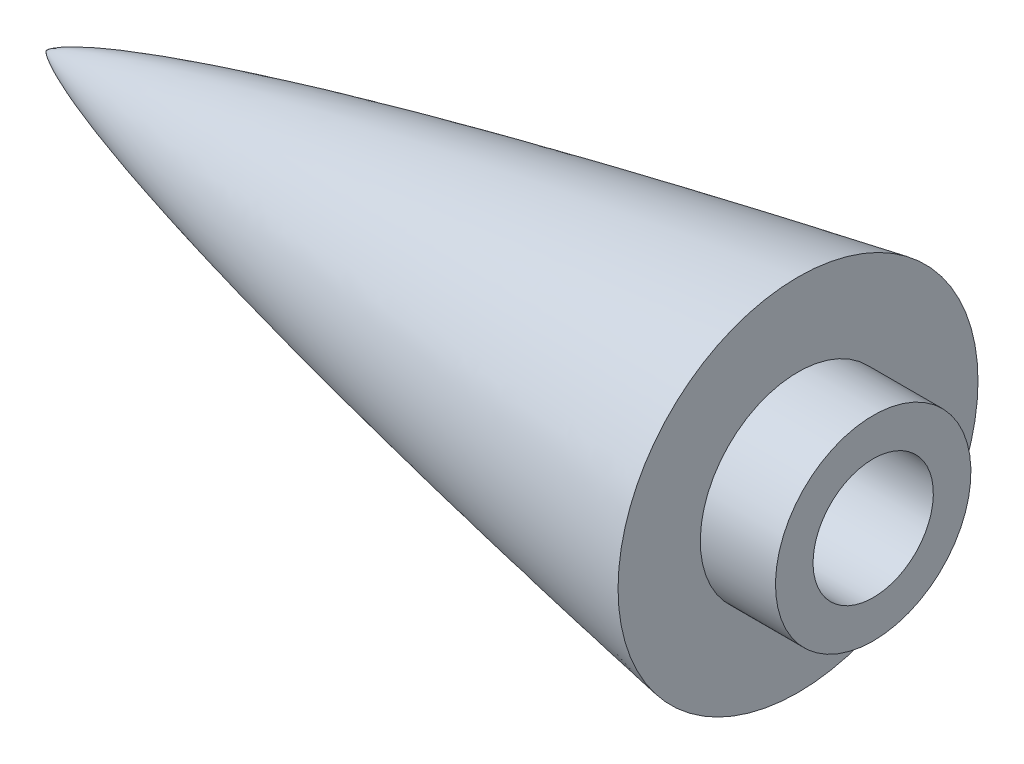
SolidWorks part; units mm, degrees
ref_plane "Front Plane" through (0, 0, 0) normal (0, 0, 1) x (1, 0, 0)
ref_plane "Top Plane" through (0, 0, 0) normal (0, 1, 0) x (1, 0, 0)
ref_plane "Right Plane" through (0, 0, 0) normal (1, 0, 0) x (0, 0, -1)
sketch "Sketch1" plane through (0, 0, 0) normal (0, 0, 1) x (1, 0, 0)
  line L0 (0.0769, 0) -> (19.7291, 0)
  line L1 (63.5769, 15.2023) -> (63.5769, 10.737)
  line L2 (63.5769, 10.737) -> (63.5769, 8.255)
  line L3 (63.5769, 8.255) -> (69.9269, 8.255)
  line L7 (19.7291, 0) -> (69.9269, 0)
  line L9 (69.9269, 8.255) -> (69.9269, 0)
  spline S0 degree 4 poles (0.0769, 0) (0.079, 0.0067) (0.0845, 0.0193) (0.099, 0.0402) (0.1222, 0.0682) (0.154, 0.101) (0.2002, 0.1434) (0.2682, 0.1995) (0.378, 0.2804) (0.559, 0.3995) (0.8654, 0.5781) (1.3931, 0.8496) (2.3104, 1.2634) (3.7858, 1.8459) (6.2747, 2.712) (9.6862, 3.7551) (13.8397, 4.9) (18.5275, 6.0876) (23.2399, 7.2065) (27.9531, 8.2687) (32.695, 9.2905) (37.4131, 10.27) (42.1916, 11.2275) (46.2904, 12.0259) (49.9453, 12.7196) (52.7752, 13.25) (55.4099, 13.7341) (57.8934, 14.19) (61.9198, 14.9103) (64.324, 15.3357) (67.702, 15.9248) (69.0842, 16.1623) (69.9374, 16.309) knots 0 0 0 0 0 0.000386 0.000771 0.001403 0.002023 0.002925 0.004255 0.006304 0.009602 0.014969 0.023966 0.039295 0.065529 0.103169 0.170438 0.237707 0.304976 0.372244 0.439513 0.506782 0.574051 0.641319 0.708588 0.742222 0.775857 0.809491 0.843126 0.910394 0.955197 1 1 1 1 1 construction
  spline S1 degree 4 poles (0.0769, 0) (0.079, 0.0067) (0.0845, 0.0193) (0.099, 0.0402) (0.1222, 0.0682) (0.154, 0.101) (0.2002, 0.1434) (0.2682, 0.1995) (0.378, 0.2804) (0.559, 0.3995) (0.8654, 0.5781) (1.3931, 0.8496) (2.3104, 1.2634) (3.7858, 1.8459) (6.2747, 2.712) (9.6862, 3.7551) (13.8397, 4.9) (18.5275, 6.0876) (23.2399, 7.2065) (27.9531, 8.2687) (32.695, 9.2905) (37.4131, 10.27) (42.1916, 11.2275) (46.2904, 12.0259) (49.9453, 12.7196) (52.7752, 13.25) (55.4099, 13.7341) (57.8934, 14.19) (60.914, 14.7304) (62.4924, 15.011) (63.5769, 15.2023) knots 0 0 0 0 0 0.000386 0.000771 0.001403 0.002023 0.002925 0.004255 0.006304 0.009602 0.014969 0.023966 0.039295 0.065529 0.103169 0.170438 0.237707 0.304976 0.372244 0.439513 0.506782 0.574051 0.641319 0.708588 0.742222 0.775857 0.809491 0.843126 0.910394 0.910394 0.910394 0.910394 0.910394
  dimension "D2" = 63.5
  dimension "D3" = 6.35
  dimension "D1" = 8.255
revolve "Revolve2" add sketch "Sketch1" angle 360 about L0
sketch "Sketch2" plane through (69.9269, 0, 0) normal (1, 0, 0) x (0, 0, -1)
  circle A0 centre (0, 0) radius 5.08
extrude "Cut-Extrude1" cut sketch "Sketch2" against normal blind 16.51
